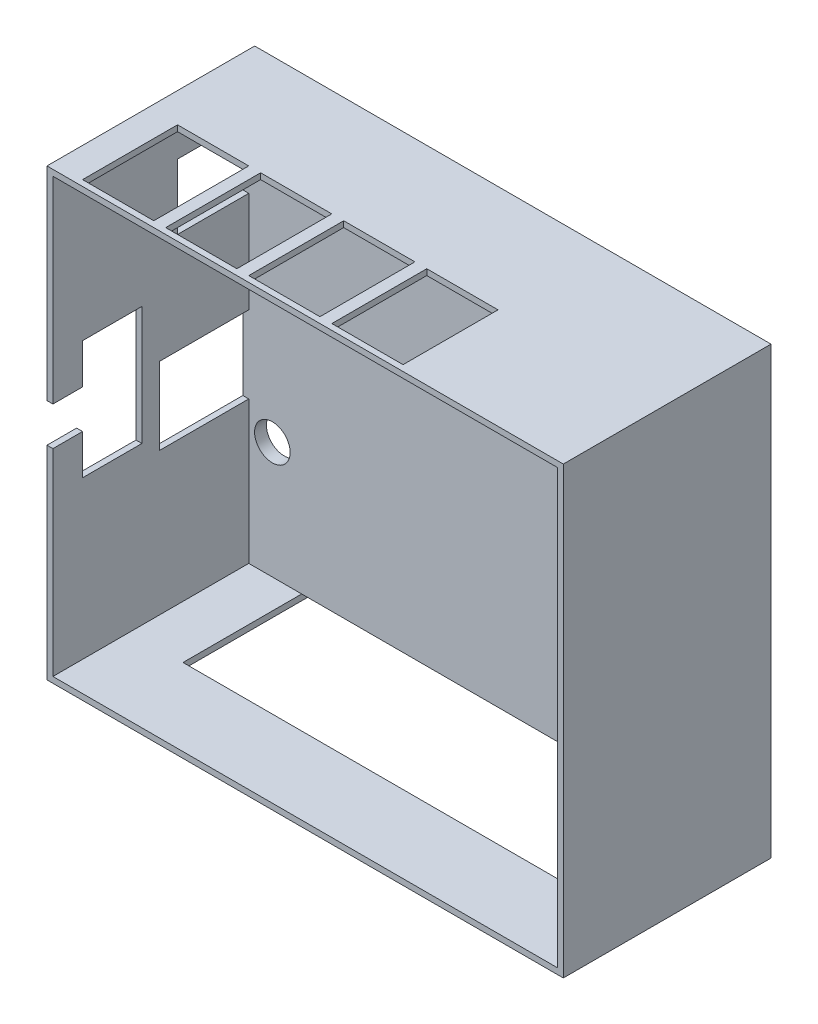
SolidWorks part; units mm, degrees
ref_plane "Plan de face" through (0, 0, 0) normal (0, 0, 1) x (1, 0, 0)
ref_plane "Plan de dessus" through (0, 0, 0) normal (0, 1, 0) x (1, 0, 0)
ref_plane "Plan de droite" through (0, 0, 0) normal (1, 0, 0) x (0, 0, -1)
sketch "Esquisse1" plane through (0, 0, 0) normal (0, 0, 1) x (1, 0, 0)
  line L1 (-132.205, 73) -> (-47.205, 73)
  line L2 (-132.205, 73) -> (-132.205, 0)
  line L3 (-132.205, 0) -> (-47.205, 0)
  line L4 (-47.205, 73) -> (-47.205, 0)
  dimension "D1" = 73
  dimension "D2" = 85
extrude "Boss.-Extru.2" add sketch "Esquisse1" along normal blind 2
sketch "Esquisse6" plane through (-47.205, 0, 0) normal (1, 0, 0) x (0, 0, -1)
  line L1 (0, 73) -> (-35, 73)
  line L2 (0, 73) -> (0, 0)
  line L3 (0, 0) -> (-35, 0)
  line L4 (-35, 73) -> (-35, 0)
  dimension "D1" = 73
  dimension "D2" = 35
extrude "Boss.-Extru.4" add sketch "Esquisse6" along normal blind 1
sketch "Esquisse8" plane through (-132.205, 0, 0) normal (-1, 0, 0) x (0, 0, 1)
  line L1 (0, 73) -> (35, 73)
  line L2 (0, 73) -> (0, 0)
  line L3 (0, 0) -> (35, 0)
  line L4 (35, 73) -> (35, 0)
extrude "Boss.-Extru.6" add sketch "Esquisse8" along normal blind 1
sketch "Esquisse10" plane through (-133.205, 0, 0) normal (-1, 0, 0) x (0, 0, 1)
  line L0 (0, 59.795) -> (2, 59.795) construction
  line L1 (2, 65) -> (14, 65)
  line L2 (2, 65) -> (2, 54)
  line L3 (2, 54) -> (14, 54)
  line L4 (14, 65) -> (14, 54)
  line L5 (0, 73) -> (0, 0) construction
  line L6 (8.5814, 73) -> (8.5814, 65) construction
  line L7 (35, 73) -> (0, 73) construction
  dimension "D1" = 11
  dimension "D2" = 12
extrude "Enlèv. mat.-Extru.1" cut sketch "Esquisse10" against normal blind 1
sketch "Esquisse11" plane through (-133.205, 0, 0) normal (-1, 0, 0) x (0, 0, 1)
  line L0 (11.1338, 0) -> (11.1338, 24) construction
  line L1 (17, 37) -> (2, 37)
  line L2 (17, 37) -> (17, 24)
  line L3 (17, 24) -> (2, 24)
  line L4 (2, 37) -> (2, 24)
  line L5 (0, 0) -> (35, 0) construction
  line L6 (2, 31.8249) -> (0, 31.8249) construction
  line L7 (0, 73) -> (0, 0) construction
  dimension "D1" = 15
  dimension "D2" = 13
extrude "Enlèv. mat.-Extru.2" cut sketch "Esquisse11" against normal blind 1
sketch "Esquisse13" plane through (0, 73, 0) normal (0, 1, 0) x (1, 0, 0)
  line L1 (-133.205, 0) -> (-46.205, 0)
  line L2 (-133.205, 0) -> (-133.205, -35)
  line L3 (-133.205, -35) -> (-46.205, -35)
  line L4 (-46.205, 0) -> (-46.205, -35)
  dimension "D1" = 35
  dimension "D2" = 87
extrude "Boss.-Extru.8" add sketch "Esquisse13" along normal blind 1
sketch "Esquisse14" plane through (0, 74, 0) normal (0, 1, 0) x (1, 0, 0)
  line L0 (-116.2799, -34) -> (-116.2799, -35) construction
  line L1 (-128.207, -18) -> (-116.207, -18)
  line L2 (-128.207, -18) -> (-128.207, -34)
  line L3 (-128.207, -34) -> (-116.207, -34)
  line L4 (-116.207, -18) -> (-116.207, -34)
  line L5 (-133.205, -35) -> (-46.205, -35) construction
  line L6 (-128.207, -21.7805) -> (-133.205, -21.7805) construction
  line L7 (-133.205, 0) -> (-133.205, -35) construction
  line L8 (-122.1939, -35) -> (-122.207, -34)
  line L9 (-123.3121, -18) -> (-123.3121, 0) construction
  line L10 (-46.205, 0) -> (-133.205, 0) construction
  dimension "D1" = 12
  dimension "D2" = 16
extrude "Enlèv. mat.-Extru.3" cut sketch "Esquisse14" against normal blind 1 contours L2 L1 L4 L3
sketch "Esquisse18" plane through (0, 74, 0) normal (0, 1, 0) x (1, 0, 0)
  line L1 (-114.207, -18) -> (-102.207, -18)
  line L2 (-114.207, -18) -> (-114.207, -34)
  line L3 (-114.207, -34) -> (-102.207, -34)
  line L4 (-102.207, -18) -> (-102.207, -34)
  line L6 (-108.207, -18) -> (-108.207, 0) construction
  line L7 (-46.205, 0) -> (-133.205, 0) construction
  line L8 (-116.207, -27.2223) -> (-114.207, -27.2223) construction
  line L9 (-116.207, -18) -> (-116.207, -34) construction
  dimension "D1" = 12
  dimension "D2" = 16
extrude "Enlèv. mat.-Extru.5" cut sketch "Esquisse18" against normal blind 1
sketch "Esquisse20" plane through (0, 74, 0) normal (0, 1, 0) x (1, 0, 0)
  line L0 (-94.6424, 0) -> (-94.6424, -18) construction
  line L1 (-100.207, -18) -> (-88.207, -18)
  line L2 (-100.207, -18) -> (-100.207, -34)
  line L3 (-100.207, -34) -> (-88.207, -34)
  line L4 (-88.207, -18) -> (-88.207, -34)
  line L5 (-46.205, 0) -> (-133.205, 0) construction
  line L6 (-100.207, -27.2382) -> (-102.207, -27.2382) construction
  line L7 (-102.207, -34) -> (-102.207, -18) construction
  dimension "D1" = 12
  dimension "D2" = 16
extrude "Enlèv. mat.-Extru.6" cut sketch "Esquisse20" against normal blind 1
sketch "Esquisse21" plane through (0, 74, 0) normal (0, 1, 0) x (1, 0, 0)
  line L0 (-81.659, 0) -> (-81.659, -18) construction
  line L1 (-86.207, -18) -> (-74.207, -18)
  line L2 (-86.207, -18) -> (-86.207, -34)
  line L3 (-86.207, -34) -> (-74.207, -34)
  line L4 (-74.207, -18) -> (-74.207, -34)
  line L5 (-46.205, 0) -> (-133.205, 0) construction
  line L6 (-86.207, -22.4048) -> (-88.207, -22.4048) construction
  line L7 (-88.207, -34) -> (-88.207, -18) construction
  dimension "D1" = 12
  dimension "D2" = 16
extrude "Enlèv. mat.-Extru.7" cut sketch "Esquisse21" against normal blind 1
sketch "Esquisse22" plane through (0, 0, 2) normal (0, 0, 1) x (1, 0, 0)
  circle A0 centre (-128.3346, 69.1704) radius 3
sketch "Esquisse23" plane through (0, 0, 2) normal (0, 0, 1) x (1, 0, 0)
  circle A0 centre (-128.2288, 19.6605) radius 3
sketch "Esquisse24" plane through (0, 0, 2) normal (0, 0, 1) x (1, 0, 0)
  line L0 (-73.2164, 69.223) -> (-74.2164, 69.223) construction
  circle A0 centre (-70.2164, 69.223) radius 3
sketch "Esquisse25" plane through (0, 0, 0) normal (0, -1, 0) x (1, 0, 0)
  line L1 (-133.205, 35) -> (-46.205, 35)
  line L2 (-133.205, 35) -> (-133.205, 0)
  line L3 (-133.205, 0) -> (-46.205, 0)
  line L4 (-46.205, 35) -> (-46.205, 0)
extrude "Boss.-Extru.11" add sketch "Esquisse25" along normal blind 1
sketch "Esquisse26" plane through (0, -1, 0) normal (0, -1, 0) x (1, 0, 0)
  line L0 (-84.786, 22) -> (-84.786, 35) construction
  line L1 (-123.286, 22) -> (-46.286, 22)
  line L2 (-123.286, 22) -> (-123.286, 0)
  line L3 (-123.286, 0) -> (-46.286, 0)
  line L4 (-46.286, 22) -> (-46.286, 0)
  line L5 (-46.205, 35) -> (-133.205, 35) construction
  dimension "D1" = 77
  dimension "D2" = 22
extrude "Enlèv. mat.-Extru.13" cut sketch "Esquisse26" against normal blind 1
extrude "Enlèv. mat.-Extru.14" cut sketch "Esquisse23" against normal blind 10
extrude "Enlèv. mat.-Extru.15" cut sketch "Esquisse22" against normal blind 10
extrude "Enlèv. mat.-Extru.18" cut sketch "Esquisse24" against normal blind 10 contours A0
sketch "Esquisse27" plane through (-133.205, 0, 0) normal (-1, 0, 0) x (0, 0, 1)
  line L0 (25, 46.5) -> (25, 74) construction
  line L1 (20, 46.5) -> (30, 46.5)
  line L2 (20, 46.5) -> (20, 26.5)
  line L3 (20, 26.5) -> (30, 26.5)
  line L4 (30, 46.5) -> (30, 26.5)
  line L5 (0, 74) -> (35, 74) construction
  line L6 (25, 26.5) -> (25, -1) construction
  line L7 (35, -1) -> (0, -1) construction
  line L8 (35, 36.5) -> (30, 36.5) construction
  line L9 (35, -1) -> (35, 74) construction
  dimension "D1" = 20
  dimension "D2" = 10
extrude "Enlèv. mat.-Extru.19" cut sketch "Esquisse27" against normal blind 1
sketch "Esquisse28" plane through (-133.205, 0, 0) normal (-1, 0, 0) x (0, 0, 1)
  line L0 (30, 26.5) -> (30, 46.5) construction
  line L1 (30, 39.75) -> (35, 39.75)
  line L2 (30, 39.75) -> (30, 33.25)
  line L3 (30, 33.25) -> (35, 33.25)
  line L4 (35, 39.75) -> (35, 33.25)
  line L5 (35, -1) -> (35, 74) construction
  line L6 (30, 46.5) -> (35, 46.5) construction
  line L7 (30, 26.5) -> (35, 26.5) construction
  line L8 (32.5, 39.75) -> (32.5, 46.5) construction
  line L9 (35, 39.75) -> (35, 74) construction
  line L10 (35, 33.25) -> (35, -1) construction
  line L11 (32.5, 33.25) -> (32.5, 26.5) construction
  dimension "D1" = 6.5
  dimension "D2" = 5
extrude "Enlèv. mat.-Extru.20" cut sketch "Esquisse28" against normal blind 10
